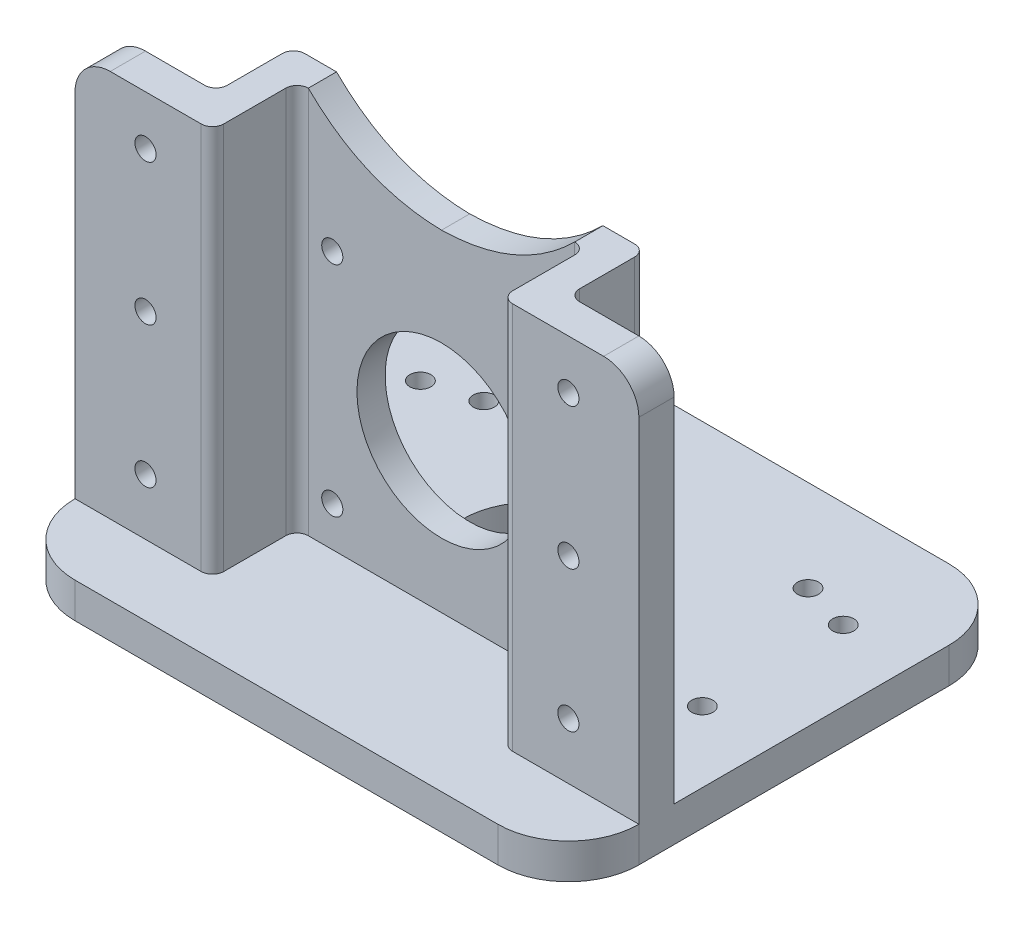
SolidWorks part; units mm, degrees
material "聚脂树脂"
ref_plane "前视基准面" through (0, 0, 0) normal (0, 0, 1) x (1, 0, 0)
ref_plane "上视基准面" through (0, 0, 0) normal (0, 1, 0) x (1, 0, 0)
ref_plane "右视基准面" through (0, 0, 0) normal (1, 0, 0) x (0, 0, -1)
other "Configuration Table"
sketch "草图1" plane through (0, 0, 0) normal (0, 1, 0) x (1, 0, 0)
  line L0 (0, 0) -> (58.6016, 0) construction
  line L1 (-40, -35) -> (40, -35)
  line L2 (-40, -35) -> (-40, 35)
  line L3 (-40, 35) -> (40, 35)
  line L4 (40, -35) -> (40, 35)
  line L5 (-40, -35) -> (40, 35) construction
  line L6 (-40, 35) -> (40, -35) construction
  line L7 (0, 0) -> (0, 47.0411) construction
  line L8 (0, 5) -> (44.8156, 5) construction
  circle A0 centre (0, 0) radius 10
  circle A1 centre (23, 16) radius 1.5
  circle A5 centre (23, -6) radius 1.5
  circle A6 centre (-23, -6) radius 1.5
  circle A7 centre (-23, 16) radius 1.5
  point P0 (0, 0)
  dimension "D3" = 20
  dimension "D4" = 3
  dimension "D7" = 11
  dimension "D1" = 70
  dimension "D2" = 80
  dimension "D5" = 23
  dimension "D6" = 5
extrude "凸台-拉伸1" add sketch "草图1" along normal blind 5
sketch "草图2" plane through (0, 5, 0) normal (0, 1, 0) x (1, 0, 0)
  line L0 (0, 0) -> (55.3583, 0) construction
  line L1 (0, 0) -> (0, 46.1954) construction
  line L2 (0, 0) -> (0, -38.3673) construction
  line L3 (-25, -9) -> (25, -9)
  line L4 (25, -9) -> (25, -20)
  line L5 (25, -20) -> (40, -20)
  line L6 (40, -20) -> (40, -25)
  line L7 (40, -25) -> (20.5, -25)
  line L8 (20.5, -25) -> (20.5, -13)
  line L9 (20.5, -13) -> (-20.5, -13)
  line L10 (-20.5, -25) -> (-20.5, -13)
  line L11 (-40, -25) -> (-20.5, -25)
  line L12 (-40, -20) -> (-40, -25)
  line L13 (-25, -20) -> (-40, -20)
  line L14 (-25, -9) -> (-25, -20)
  point P14 (0, -13)
  point P19 (0, -9)
  dimension "D1" = 25
  dimension "D2" = 11
  dimension "D3" = 20.5
  dimension "D4" = 12
  dimension "D5" = 19.5
  dimension "D6" = 9
  dimension "D7" = 4
extrude "凸台-拉伸2" add sketch "草图2" along normal blind 55
sketch "草图3" plane through (0, 0, 13) normal (0, 0, 1) x (1, 0, 0)
  line L0 (0, 0) -> (0, 69.1059) construction
  line L1 (0, 0) -> (57.4199, 0) construction
  line L2 (0, 5) -> (40.8093, 5) construction
  line L3 (-40, 5) -> (40, 5) construction
  line L4 (0, 26.15) -> (45.791, 26.15) construction
  line L5 (-30, 13) -> (-30, 61.5047) construction
  line L6 (-40, 5) -> (-20.5, 5) construction
  circle A0 centre (0, 26.15) radius 12
  circle A1 centre (15.5, 41.65) radius 1.5
  circle A2 centre (15.5, 10.65) radius 1.5
  circle A3 centre (-15.5, 10.65) radius 1.5
  circle A4 centre (-15.5, 41.65) radius 1.5
  circle A5 centre (-30, 13) radius 1.5
  circle A6 centre (-30, 33) radius 1.5
  circle A7 centre (-30, 53) radius 1.5
  circle A8 centre (30, 53) radius 1.5
  circle A9 centre (30, 33) radius 1.5
  circle A10 centre (30, 13) radius 1.5
  dimension "D2" = 24
  dimension "D3" = 3
  dimension "D4" = 31
  dimension "D5" = 31
  dimension "D6" = 3
  dimension "D7" = 3
  dimension "D8" = 3
  dimension "D9" = 20
  dimension "D10" = 20
  dimension "D11" = 8
  dimension "D1" = 21.15
  dimension "D12" = 30
extrude "切除-拉伸1" cut sketch "草图3" along normal blind 60 and the other way blind 60
fillet "圆角3" radius 1.6 8 edges at (20.5, 32.5, 25) (20.5, 32.5, 13) (-20.5, 32.5, 25) (-20.5, 32.5, 13) (25, 32.5, 20) (25, 32.5, 9) (-25, 32.5, 9) (-25, 32.5, 20)
sketch "草图4" plane through (0, 5, 0) normal (0, 1, 0) x (1, 0, 0)
  line L0 (0, 0) -> (50.2662, 0) construction
  line L1 (0, 0) -> (0, 50.3436) construction
  line L2 (30, -23.9509) -> (30, 23.9509) construction
  circle A0 centre (30, 14) radius 1.5
  circle A1 centre (30, -6) radius 1.5
  circle A2 centre (-30, -6) radius 1.5
  circle A3 centre (-30, 14) radius 1.5
  point P11 (30, 0)
  point P17 (-30, 0)
  dimension "D1" = 3
  dimension "D2" = 3
  dimension "D3" = 20
  dimension "D4" = 14
  dimension "D5" = 30
extrude "切除-拉伸2" cut sketch "草图4" against normal blind 10
sketch "草图5" plane through (0, 5, 0) normal (0, 1, 0) x (1, 0, 0)
  line L0 (-40, 29) -> (-40, 35)
  line L1 (-40, 35) -> (-40, -20) construction
  line L2 (-40, 35) -> (40, 35)
  line L3 (40, 35) -> (40, 29)
  line L4 (40, -20) -> (40, 35) construction
  line L5 (40, 29) -> (-40, 29)
  dimension "D1" = 6
extrude "切除-拉伸3" cut sketch "草图5" against normal blind 10
fillet "圆角4" radius 10 4 edges at (40, 2.5, -29) (-40, 2.5, -29) (40, 2.5, 35) (-40, 2.5, 35)
sketch "草图6" plane through (0, 0, 13) normal (0, 0, 1) x (1, 0, 0)
  line L0 (0, 0) -> (0, 81.7287) construction
  line L1 (18.9, 60) -> (-18.9, 60)
  spline S0 degree 2 poles (-18.9, 60) (-11.0346, 52.2022) (0, 52) knots 0 0 0 1 1 1
  spline S1 degree 2 poles (18.9, 60) (11.0346, 52.2022) (0, 52) knots 0 0 0 1 1 1
  dimension "D1" = 8
  dimension "D2" = 6
  dimension "D3" = 10
extrude "切除-拉伸4" cut sketch "草图6" against normal blind 10
fillet "圆角5" radius 5 2 edges at (40, 60, 22.5) (-40, 60, 22.5)
